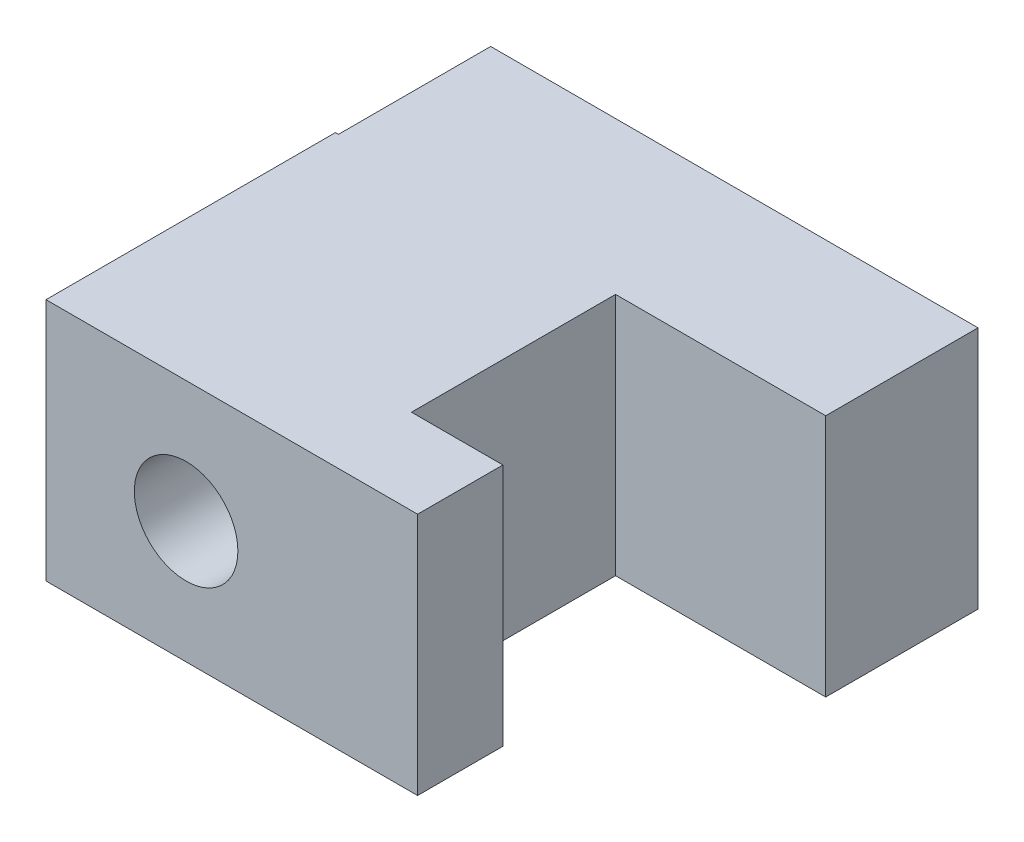
SolidWorks part; units mm, degrees
ref_plane "前视基准面" through (0, 0, 0) normal (0, 0, 1) x (1, 0, 0)
ref_plane "上视基准面" through (0, 0, 0) normal (0, 1, 0) x (1, 0, 0)
ref_plane "右视基准面" through (0, 0, 0) normal (1, 0, 0) x (0, 0, -1)
other "Configuration Table"
sketch "Sketch_Foot_and_support_shelf" plane through (0, 0, 0) normal (0, 0, 1) x (1, 0, 0)
  line L0 (11.5, -4) -> (11.5, 4)
  line L1 (11.5, 4) -> (-4.5, 4)
  line L2 (-4.5, 4) -> (-4.5, -4)
  line L3 (-4.5, -4) -> (11.5, -4)
extrude "Foot_and_support_shelf" add sketch "Sketch_Foot_and_support_shelf" along normal blind 5 from offset 0
sketch "Sketch_Clamp_upright" plane through (0, 0, 0) normal (0, 0, 1) x (1, 0, 0)
  line L0 (4.6, -4) -> (4.6, 4)
  line L1 (4.6, 4) -> (-4.6, 4)
  line L2 (-4.6, 4) -> (-4.6, -4)
  line L3 (-4.6, -4) -> (4.6, -4)
extrude "Clamp_upright" add sketch "Sketch_Clamp_upright" along normal blind 6.7 from offset 5
sketch "Sketch_Corner_retaining_lip" plane through (0, 0, 0) normal (0, 0, 1) x (1, 0, 0)
  line L0 (7.6, -4) -> (7.6, 4)
  line L1 (7.6, 4) -> (-4.6, 4)
  line L2 (-4.6, 4) -> (-4.6, -4)
  line L3 (-4.6, -4) -> (7.6, -4)
extrude "Corner_retaining_lip" add sketch "Sketch_Corner_retaining_lip" along normal blind 2.8 from offset 11.7
sketch "Sketch_M3_through" plane through (0, 0, 0) normal (0, 0, 1) x (1, 0, 0)
  circle A0 centre (0, 0) radius 1.7
  dimension "D1" = 3.4
extrude "M3_through" cut sketch "Sketch_M3_through" along normal blind 17 from offset 1
